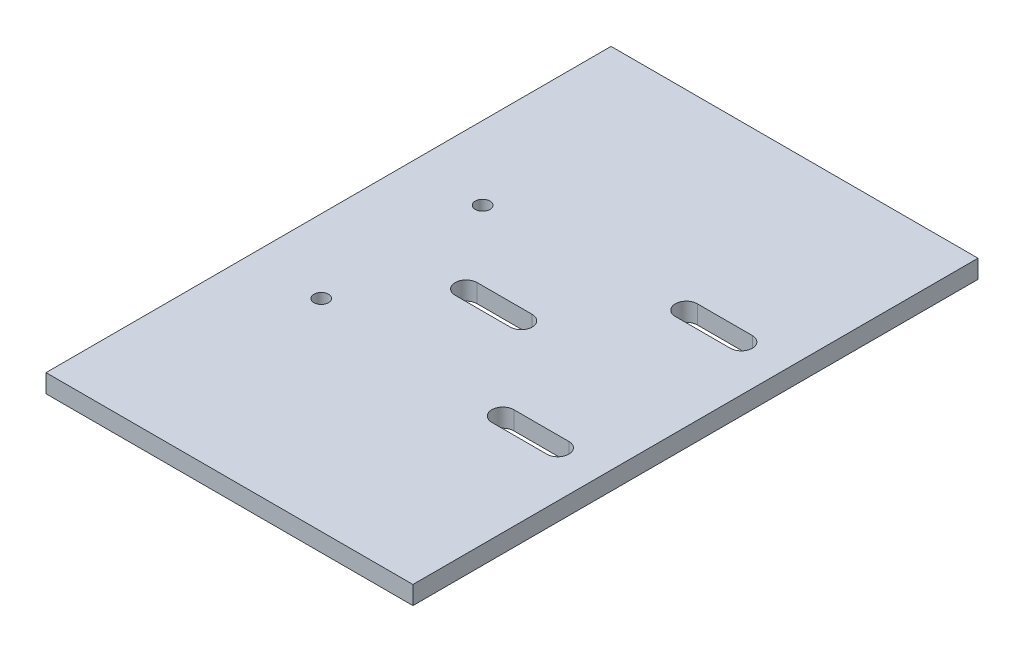
SolidWorks part; units mm, degrees
ref_plane "Front Plane" through (0, 0, 0) normal (0, 0, 1) x (1, 0, 0)
ref_plane "Top Plane" through (0, 0, 0) normal (0, 1, 0) x (1, 0, 0)
ref_plane "Right Plane" through (0, 0, 0) normal (1, 0, 0) x (0, 0, -1)
sketch "Sketch1" plane through (0, 0, 0) normal (0, 1, 0) x (1, 0, 0)
  line L0 (73.3491, 51.6462) -> (19.3491, 51.6462) construction
  line L1 (-26.6509, 128.6462) -> (73.3491, 128.6462)
  line L2 (-26.6509, 128.6462) -> (-26.6509, -25.3538)
  line L3 (-26.6509, -25.3538) -> (73.3491, -25.3538)
  line L4 (73.3491, 128.6462) -> (73.3491, -25.3538)
  line L5 (7.3491, 51.6462) -> (-26.6509, 51.6462) construction
  line L6 (73.3491, 51.6462) -> (-26.6509, 51.6462) construction
  line L7 (45.8491, 76.6462) -> (60.8491, 76.6462) construction
  line L8 (45.8491, 79.6462) -> (60.8491, 79.6462)
  line L9 (45.8491, 73.6462) -> (60.8491, 73.6462)
  line L10 (10.8491, 51.6462) -> (25.8491, 51.6462) construction
  line L11 (10.8491, 54.6462) -> (25.8491, 54.6462)
  line L12 (10.8491, 48.6462) -> (25.8491, 48.6462)
  line L13 (45.8491, 26.6462) -> (60.8491, 26.6462) construction
  line L14 (45.8491, 29.6462) -> (60.8491, 29.6462)
  line L15 (45.8491, 23.6462) -> (60.8491, 23.6462)
  circle A2 centre (18.3491, 51.6462) radius 3 construction
  circle A3 centre (53.3491, 76.6462) radius 3 construction
  circle A4 centre (53.3491, 26.6462) radius 3 construction
  arc A5 (45.8491, 79.6462) -> (45.8491, 73.6462) centre (45.8491, 76.6462) ccw
  arc A6 (60.8491, 73.6462) -> (60.8491, 79.6462) centre (60.8491, 76.6462) ccw
  arc A7 (10.8491, 54.6462) -> (10.8491, 48.6462) centre (10.8491, 51.6462) ccw
  arc A8 (25.8491, 48.6462) -> (25.8491, 54.6462) centre (25.8491, 51.6462) ccw
  arc A9 (45.8491, 29.6462) -> (45.8491, 23.6462) centre (45.8491, 26.6462) ccw
  arc A10 (60.8491, 23.6462) -> (60.8491, 29.6462) centre (60.8491, 26.6462) ccw
  circle A11 centre (-6.6509, 73.6462) radius 2
  circle A12 centre (-6.6509, 29.6462) radius 2
  point P16 (53.3491, 76.6462)
  point P23 (18.3491, 51.6462)
  point P30 (53.3491, 26.6462)
  dimension "D3" = 6
  dimension "D4" = 6
  dimension "D9" = 3
  dimension "D11" = 3
  dimension "D13" = 3
  dimension "D14" = 4
  dimension "D1" = 154
  dimension "D2" = 100
  dimension "D5" = 55
  dimension "D6" = 20
  dimension "D7" = 25
  dimension "D8" = 15
  dimension "D10" = 15
  dimension "D12" = 15
  dimension "D15" = 22
  dimension "D16" = 20
extrude "Boss-Extrude1" add sketch "Sketch1" along normal blind 5
